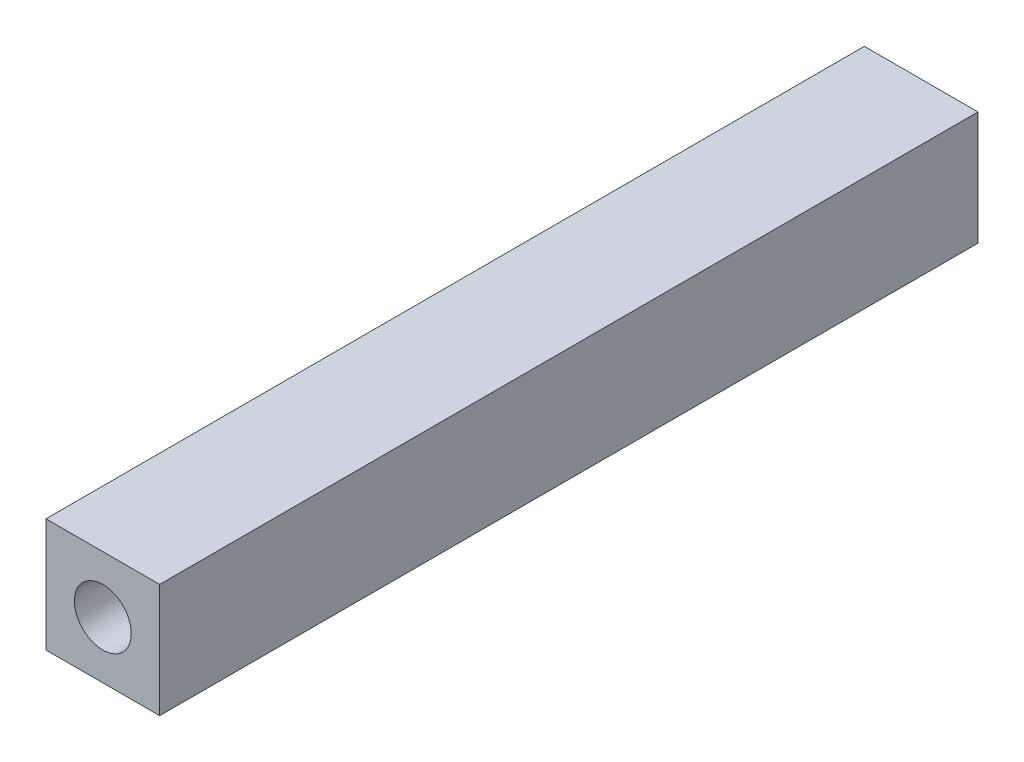
SolidWorks part; units mm, degrees
ref_plane "Front Plane" through (0, 0, 0) normal (0, 0, 1) x (1, 0, 0)
ref_plane "Top Plane" through (0, 0, 0) normal (0, 1, 0) x (1, 0, 0)
ref_plane "Right Plane" through (0, 0, 0) normal (1, 0, 0) x (0, 0, -1)
sketch "Sketch1" plane through (0, 0, 0) normal (0, 0, 1) x (1, 0, 0)
  line L1 (-25, -25) -> (25, -25)
  line L2 (-25, -25) -> (-25, 25)
  line L3 (-25, 25) -> (25, 25)
  line L4 (25, -25) -> (25, 25)
  line L5 (-25, -25) -> (25, 25) construction
  line L6 (-25, 25) -> (25, -25) construction
  line L7 (-20, -20) -> (20, -20)
  line L8 (-20, -20) -> (-20, 20)
  line L9 (-20, 20) -> (20, 20)
  line L10 (20, -20) -> (20, 20)
  line L11 (-20, -20) -> (20, 20) construction
  line L12 (-20, 20) -> (20, -20) construction
  circle A0 centre (0, 0) radius 12.5
  point P0 (0, 0)
  point P6 (0, 0)
  dimension "D4" = 25
  dimension "D1" = 50
  dimension "0" = 50
  dimension "D2" = 40
  dimension "D3" = 40
extrude "Boss-Extrude1" add sketch "Sketch1" along normal blind 360 contours L1 L4 L3 L2 L10 L7 L8 L9 | A0 L10 L9 | A0 L9 L8 | A0 L8 L7 | A0 L7 L10
